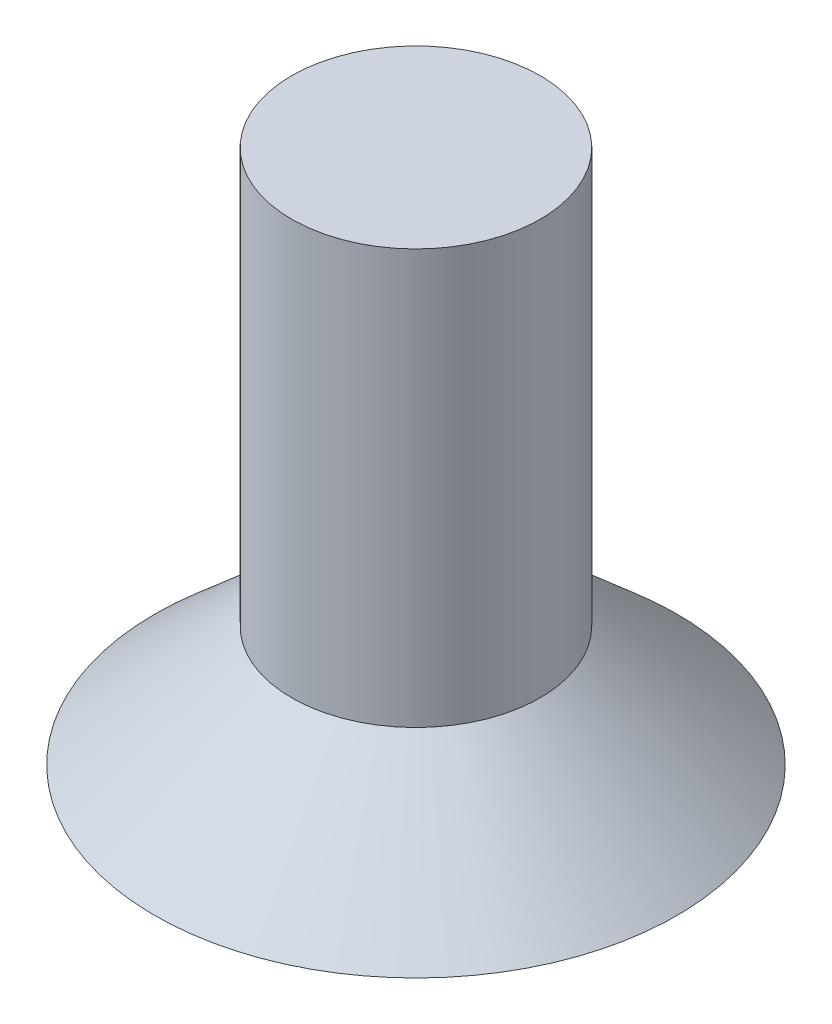
SolidWorks part; units mm, degrees
material "Plain Carbon Steel"
ref_plane "Front Plane" through (0, 0, 0) normal (0, 0, 1) x (1, 0, 0)
ref_plane "Top Plane" through (0, 0, 0) normal (0, 1, 0) x (1, 0, 0)
ref_plane "Right Plane" through (0, 0, 0) normal (1, 0, 0) x (0, 0, -1)
sketch "Sketch1" plane through (0, 0, 0) normal (0, 0, 1) x (1, 0, 0)
  line L0 (0, 0) -> (3.15, 0)
  line L1 (3.15, 0) -> (1.5, 1.45)
  line L2 (1.5, 1.45) -> (1.5, 6.45)
  line L3 (1.5, 6.45) -> (0, 6.45)
  line L4 (0, 6.45) -> (0, 0)
  dimension "D1" = 3.15
  dimension "D2" = 1.5
  dimension "D3" = 1.45
  dimension "D4" = 5
revolve "Revolve1" add sketch "Sketch1" angle 360 about L4
